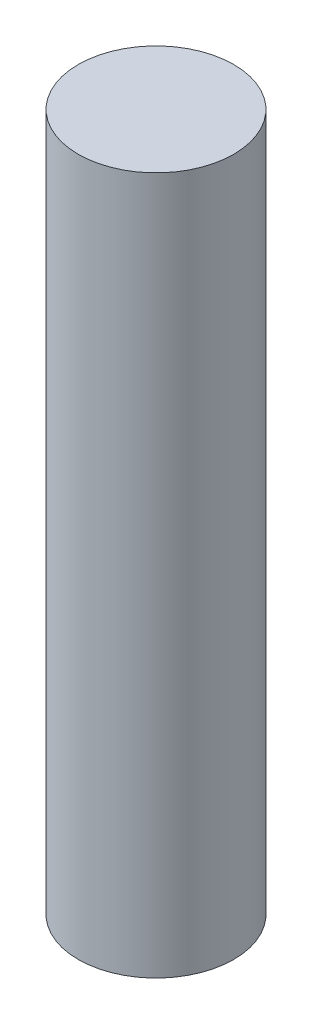
SolidWorks part; units mm, degrees
material "AISI 4340 Acero recocido"
ref_plane "Alzado" through (0, 0, 0) normal (0, 0, 1) x (1, 0, 0)
ref_plane "Planta" through (0, 0, 0) normal (0, 1, 0) x (1, 0, 0)
ref_plane "Vista lateral" through (0, 0, 0) normal (1, 0, 0) x (0, 0, -1)
sketch "Croquis1" plane through (0, 0, 0) normal (0, 1, 0) x (1, 0, 0)
  circle A0 centre (0, 0) radius 564.2
  dimension "D1" = 1128.4
extrude "Saliente-Extruir1" add sketch "Croquis1" along normal blind 5060
